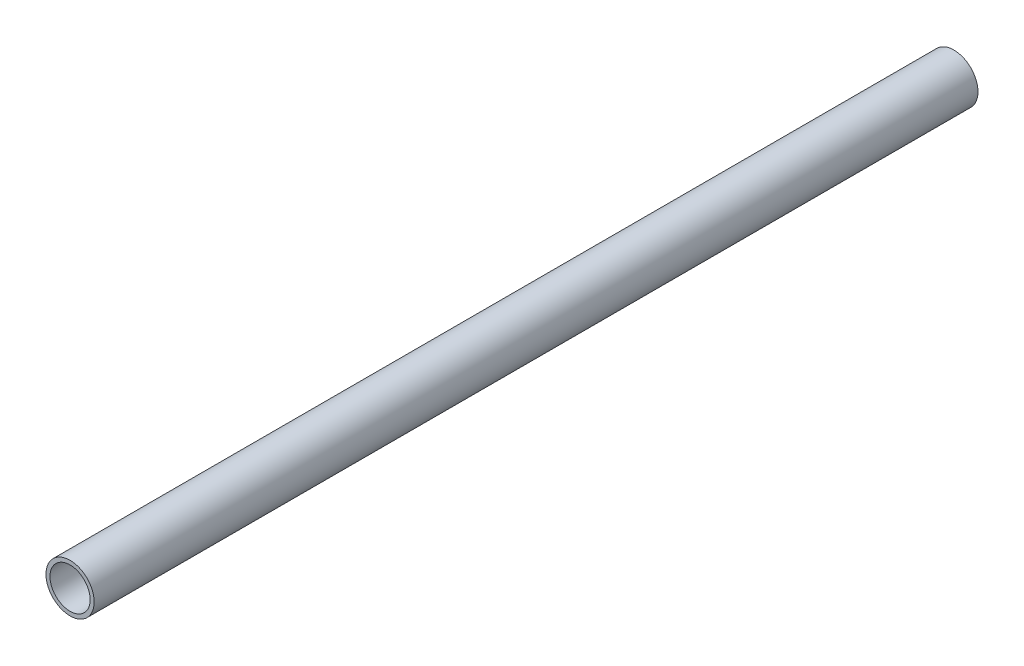
SolidWorks part; units mm, degrees
ref_plane "Front Plane" through (0, 0, 0) normal (0, 0, 1) x (1, 0, 0)
ref_plane "Top Plane" through (0, 0, 0) normal (0, 1, 0) x (1, 0, 0)
ref_plane "Right Plane" through (0, 0, 0) normal (1, 0, 0) x (0, 0, -1)
sketch "Sketch1" plane through (0, 0, 0) normal (0, 0, 1) x (1, 0, 0)
  circle A0 centre (0, 0) radius 6
  circle A1 centre (0, 0) radius 5
  dimension "D1" = 12
  dimension "D2" = 10
extrude "Boss-Extrude1" add sketch "Sketch1" along normal blind 220
